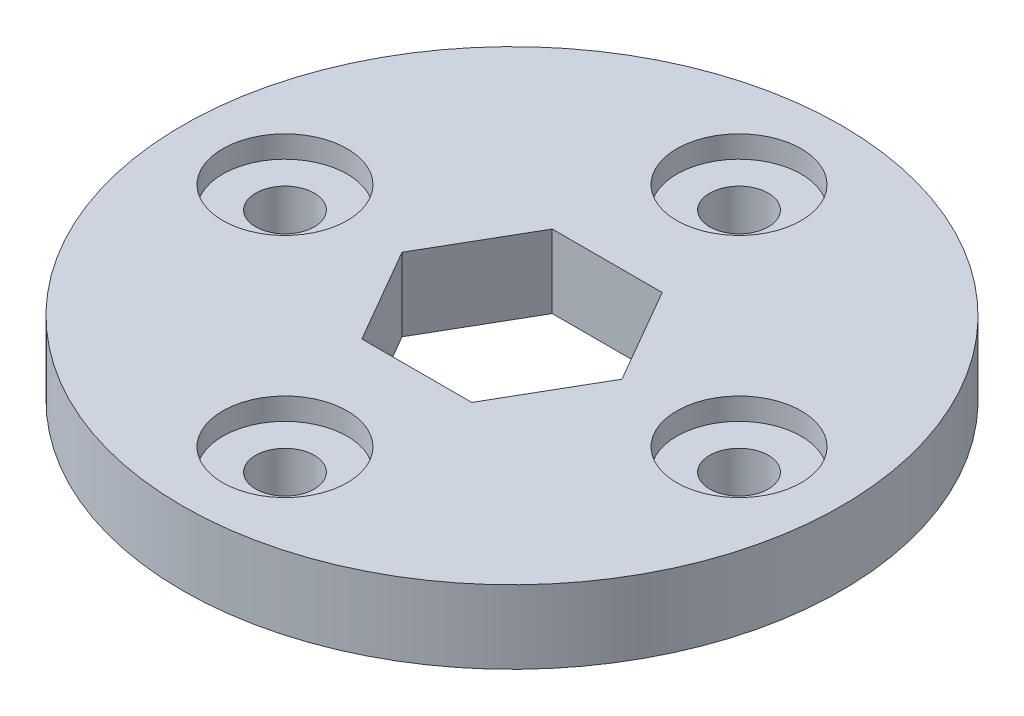
SolidWorks part; units mm, degrees
ref_plane "Front Plane" through (0, 0, 0) normal (0, 0, 1) x (1, 0, 0)
ref_plane "Top Plane" through (0, 0, 0) normal (0, 1, 0) x (1, 0, 0)
ref_plane "Right Plane" through (0, 0, 0) normal (1, 0, 0) x (0, 0, -1)
sketch "Sketch1" plane through (0, 0, 0) normal (0, 1, 0) x (1, 0, 0)
  line L1 (7.5056, 0) -> (3.7528, 6.5)
  line L2 (3.7528, 6.5) -> (-3.7528, 6.5)
  line L3 (-3.7528, 6.5) -> (-7.5056, 0)
  line L4 (-7.5056, 0) -> (-3.7528, -6.5)
  line L5 (-3.7528, -6.5) -> (3.7528, -6.5)
  line L6 (3.7528, -6.5) -> (7.5056, 0)
  circle A0 centre (0, 0) radius 22.5
  circle A1 centre (0, 0) radius 15.5 construction
  circle A2 centre (0, 0) radius 6.5 construction
  circle A3 centre (0, 15.5) radius 2
  circle A4 centre (15.5, 0) radius 2
  circle A5 centre (0, -15.5) radius 2
  circle A6 centre (-15.5, 0) radius 2
  point P26 (0, 0)
  dimension "D1" = 45
  dimension "D2" = 31
  dimension "D4" = 4
  dimension "D3" = 13
  dimension "D5" = 4
extrude "Boss-Extrude1" add sketch "Sketch1" along normal blind 5
sketch "Sketch2" plane through (0, 5, 0) normal (0, 1, 0) x (1, 0, 0)
  circle A0 centre (0, 0) radius 15.5 construction
  circle A1 centre (0, 15.5) radius 4.25
  circle A2 centre (15.5, 0) radius 4.25
  circle A3 centre (0, -15.5) radius 4.25
  circle A4 centre (-15.5, 0) radius 4.25
  point P7 (0, 0)
  point P18 (0, 0)
  dimension "D1" = 8.5
  dimension "D3" = 31
  dimension "D2" = 4
extrude "Cut-Extrude1" cut sketch "Sketch2" against normal blind 1.5
